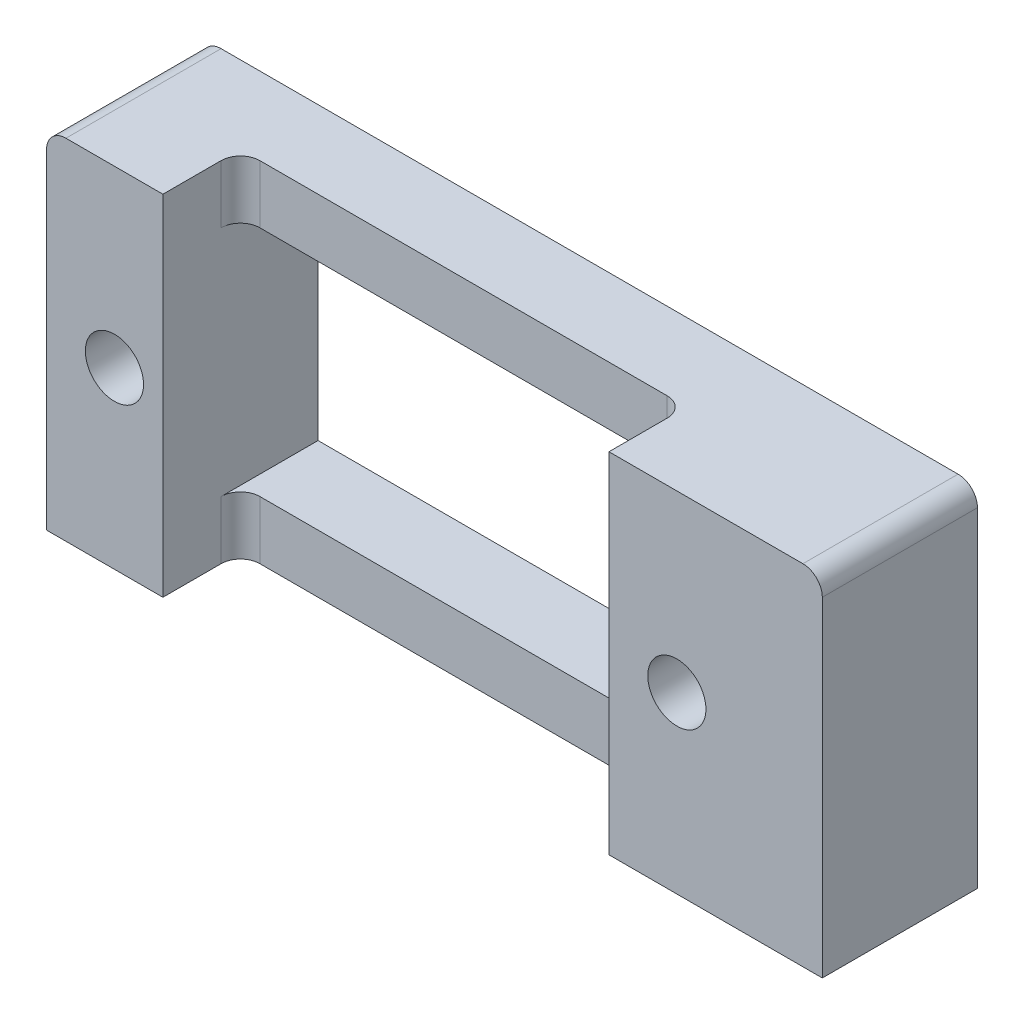
SolidWorks part; units mm, degrees
ref_plane "Front Plane" through (0, 0, 0) normal (0, 0, 1) x (1, 0, 0)
ref_plane "Top Plane" through (0, 0, 0) normal (0, 1, 0) x (1, 0, 0)
ref_plane "Right Plane" through (0, 0, 0) normal (1, 0, 0) x (0, 0, -1)
sketch "Sketch1" plane through (0, 0, 0) normal (0, 0, 1) x (1, 0, 0)
  line L0 (-15.9239, 0.6033) -> (24.0761, 0.6033) construction
  line L1 (-15.9239, 9.6033) -> (24.0761, 9.6033)
  line L2 (-15.9239, 9.6033) -> (-15.9239, -8.3967)
  line L3 (-15.9239, -8.3967) -> (24.0761, -8.3967)
  line L4 (24.0761, 9.6033) -> (24.0761, -8.3967)
  line L5 (-15.9239, -8.3967) -> (-9.9239, -8.3967)
  line L6 (-15.9239, -8.3967) -> (-15.9239, 9.6033)
  line L7 (-15.9239, 9.6033) -> (-9.9239, 9.6033)
  line L8 (-9.9239, -5.3967) -> (-9.9239, 6.6033)
  line L9 (24.0761, -8.3967) -> (13.0761, -8.3967)
  line L10 (24.0761, -8.3967) -> (24.0761, 9.6033)
  line L11 (24.0761, 9.6033) -> (13.0761, 9.6033)
  line L12 (13.0761, -5.3967) -> (13.0761, 6.6033)
  line L13 (-15.9239, -8.3967) -> (24.0761, -8.3967)
  line L14 (-15.9239, -8.3967) -> (-15.9239, -5.3967)
  line L15 (-9.9239, -5.3967) -> (13.0761, -5.3967)
  line L16 (24.0761, -8.3967) -> (24.0761, -5.3967)
  line L17 (-15.9239, 9.6033) -> (24.0761, 9.6033)
  line L18 (-15.9239, 9.6033) -> (-15.9239, 6.6033)
  line L19 (-9.9239, 6.6033) -> (13.0761, 6.6033)
  line L20 (24.0761, 9.6033) -> (24.0761, 6.6033)
  circle A0 centre (-12.4239, 0.6033) radius 1.5
  circle A1 centre (16.5761, 0.6033) radius 1.5
  dimension "D8" = 3
  dimension "D10" = 3
  dimension "D1" = 18
  dimension "D2" = 40
  dimension "D3" = 6
  dimension "D4" = 11
  dimension "D5" = 3
  dimension "D6" = 3
  dimension "D7" = 23
  dimension "D9" = 2.5
  dimension "D11" = 29
extrude "Boss-Extrude1" add sketch "Sketch1" against normal blind 8 contours L6 L0 A0 L8 L19 L12 A1 L10 L4 L1 L2 | L0 L2 L6 L3 L10 L4 A1 L12 L15 L8 A0
sketch "Sketch2" plane through (0, 0, 0) normal (0, 0, 1) x (1, 0, 0)
  line L0 (-15.9239, 9.6033) -> (24.0761, 9.6033) construction
  line L1 (-9.9239, 6.6033) -> (13.0761, 6.6033)
  line L2 (-9.9239, 6.6033) -> (-9.9239, 9.6033)
  line L3 (-9.9239, 9.6033) -> (13.0761, 9.6033)
  line L4 (13.0761, 6.6033) -> (13.0761, 9.6033)
  line L5 (-15.9239, -8.3967) -> (24.0761, -8.3967) construction
  line L6 (-9.9239, -5.3967) -> (13.0761, -5.3967)
  line L7 (-9.9239, -5.3967) -> (-9.9239, -8.3967)
  line L8 (-9.9239, -8.3967) -> (13.0761, -8.3967)
  line L9 (13.0761, -5.3967) -> (13.0761, -8.3967)
extrude "Cut-Extrude1" cut sketch "Sketch2" against normal blind 4
fillet "Fillet1" radius 1 4 edges at (13.0761, -6.8967, -4) (13.0761, 8.1033, -4) (-9.9239, 8.1033, -4) (-9.9239, -6.8967, -4)
fillet "Fillet2" radius 1 2 edges at (24.0761, 9.6033, -4) (-15.9239, 9.6033, -4)
